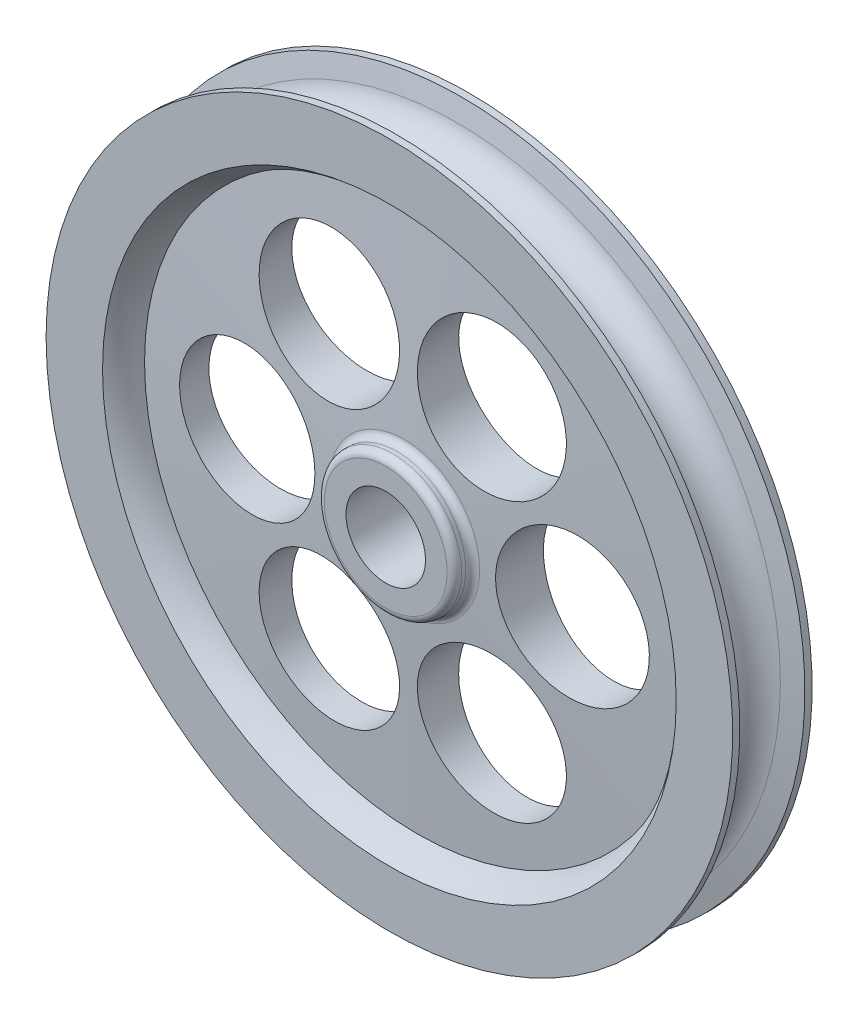
SolidWorks part; units mm, degrees
ref_plane "Front Plane" through (0, 0, 0) normal (0, 0, 1) x (1, 0, 0)
ref_plane "Top Plane" through (0, 0, 0) normal (0, 1, 0) x (1, 0, 0)
ref_plane "Right Plane" through (0, 0, 0) normal (1, 0, 0) x (0, 0, -1)
sketch "Sketch1" plane through (0, 0, 0) normal (0, 1, 0) x (1, 0, 0)
  line L17 (11, 12) -> (11, 24)
  line L18 (20.8722, 18.8801) -> (75.3633, 15.39)
  line L19 (95, 3) -> (95, 1)
  line L20 (95, 1) -> (79.381, 1)
  line L21 (95, 3) -> (89.3752, 4.1667)
  line L22 (19, 22) -> (19, 20.876)
  line L23 (11, 24) -> (17, 24)
  line L24 (11, 0) -> (17, 0)
  line L25 (19, 2) -> (19, 3.124)
  line L26 (20.8722, 5.1199) -> (75.3633, 8.61)
  line L27 (0, 12) -> (0, 0)
  line L28 (11, 12) -> (11, 0)
  line L29 (95, 21) -> (89.3752, 19.8333)
  line L30 (95, 23) -> (79.381, 23)
  line L31 (95, 21) -> (95, 23)
  arc A7 (89.3752, 19.8333) -> (89.3752, 4.1667) centre (91, 12) ccw
  arc A8 (75.3633, 8.61) -> (79.381, 1) centre (91, 12) ccw
  arc A9 (17, 0) -> (19, 2) centre (17, 2) ccw
  arc A10 (19, 3.124) -> (20.8722, 5.1199) centre (21, 3.124) cw
  arc A11 (19, 20.876) -> (20.8722, 18.8801) centre (21, 20.876) ccw
  arc A12 (17, 24) -> (19, 22) centre (17, 22) cw
  arc A13 (75.3633, 15.39) -> (79.381, 23) centre (91, 12) cw
  dimension "D1" = 12
  dimension "D2" = 2
  dimension "D3" = 11
revolve "Revolve2" add sketch "Sketch1" angle 360 about L27
sketch "Sketch3" plane through (0, 0, 0) normal (0, 0, 1) x (1, 0, 0)
  circle A1 centre (45, 0) radius 20
  circle A2 centre (22.5, -38.9711) radius 20
  circle A3 centre (-22.5, -38.9711) radius 20
  circle A4 centre (-45, 0) radius 20
  circle A5 centre (-22.5, 38.9711) radius 20
  circle A6 centre (22.5, 38.9711) radius 20
  dimension "D1" = 6
extrude "Cut-Extrude1" cut sketch "Sketch3" against normal blind 30
